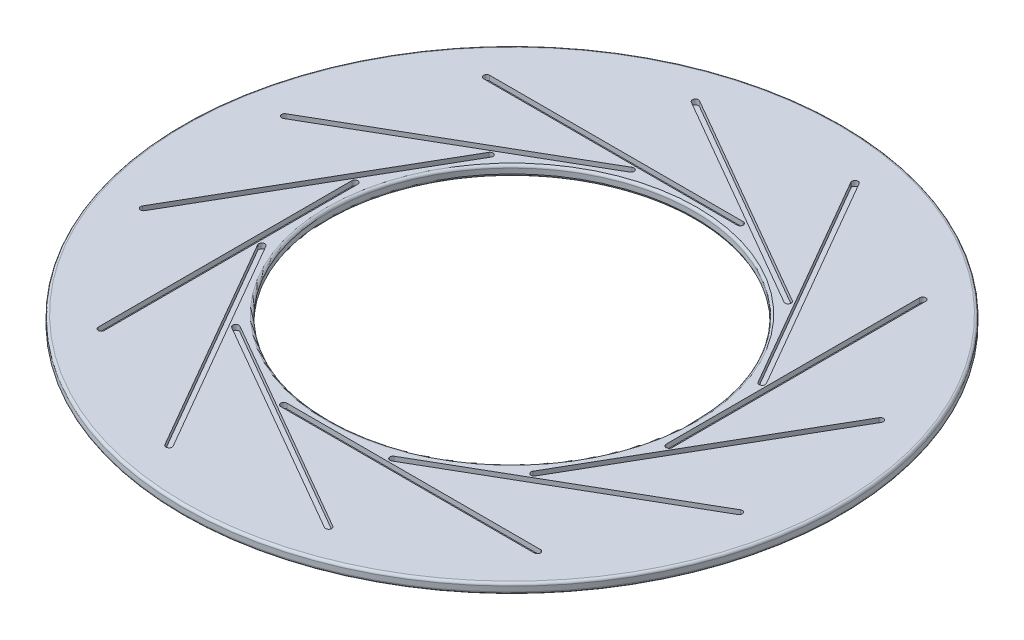
SolidWorks part; units mm, degrees
ref_plane "Front Plane" through (0, 0, 0) normal (0, 0, 1) x (1, 0, 0)
ref_plane "Top Plane" through (0, 0, 0) normal (0, 1, 0) x (1, 0, 0)
ref_plane "Right Plane" through (0, 0, 0) normal (1, 0, 0) x (0, 0, -1)
sketch "Sketch2" plane through (0, 0, 0) normal (0, 1, 0) x (1, 0, 0)
  circle A0 centre (0, 0) radius 36
  circle A1 centre (0, 0) radius 65
  dimension "D1" = 72
  dimension "D2" = 130
extrude "ring extrusion" add sketch "Sketch2" along normal blind 2
sketch "Sketch5" plane through (0, 2, 0) normal (0, 1, 0) x (1, 0, 0)
  line L0 (0, 65) -> (0, 0) construction
  line L1 (-43, 38) -> (7, 38) construction
  line L2 (-43, 38.6) -> (7, 38.6)
  line L3 (-43, 37.4) -> (7, 37.4)
  circle A0 centre (0, 0) radius 38 construction
  arc A1 (-43, 38.6) -> (-43, 37.4) centre (-43, 38) ccw
  arc A2 (7, 37.4) -> (7, 38.6) centre (7, 38) ccw
  circle A3 centre (0, 0) radius 65 construction
  point P6 (-18, 38)
  dimension "D1" = 76
  dimension "D2" = 0.6
  dimension "D3" = 50
  dimension "D4" = 7
extrude "grooves" cut sketch "Sketch5" against normal blind 1
pattern_circular "CirPattern2" count 12 over 360 about axis through (0, 0, 0) along (0, 1, 0) of "grooves"
fillet "Fillet3" radius 0.5 4 edges at (0, 2, 65) (0, 0, 65) (0, 2, 36) (0, 0, 36)
equation "\"D1@CirPattern2\"=\"grooves@Shutter Assembly.Assembly\""
